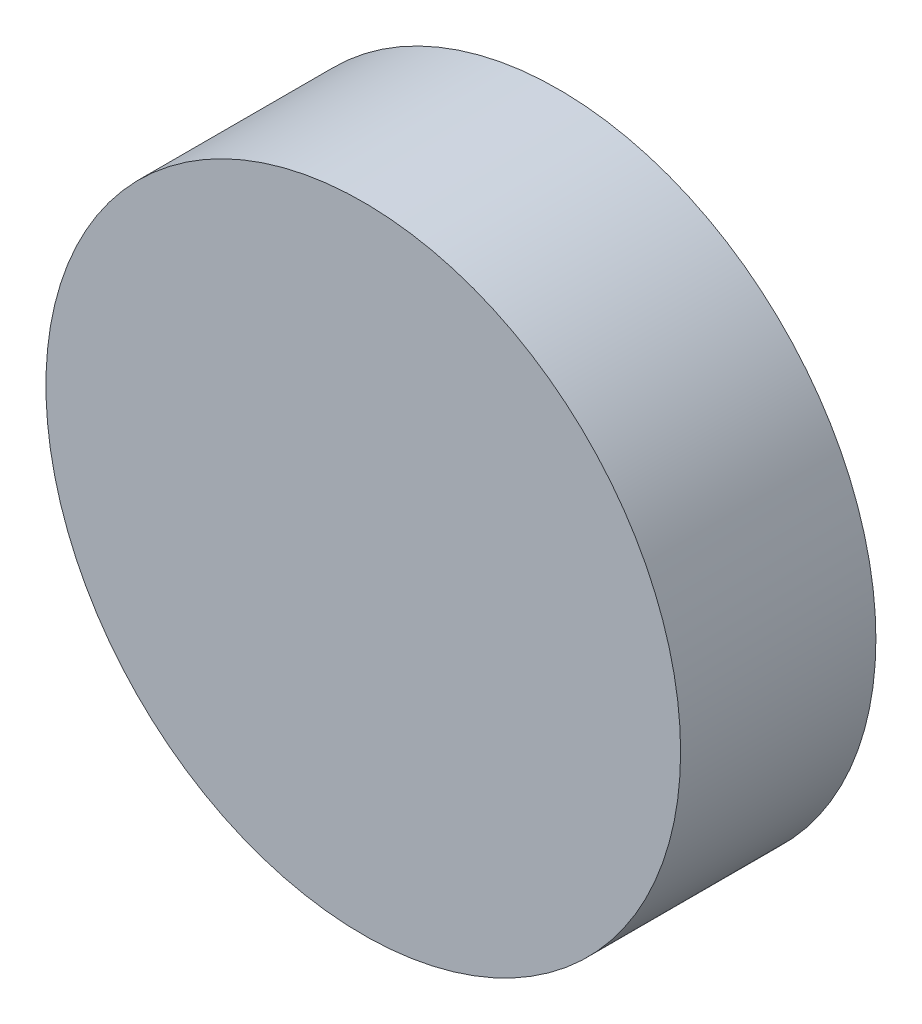
SolidWorks part; units mm, degrees
ref_plane "前视基准面" through (0, 0, 0) normal (0, 0, 1) x (1, 0, 0)
ref_plane "上视基准面" through (0, 0, 0) normal (0, 1, 0) x (1, 0, 0)
ref_plane "右视基准面" through (0, 0, 0) normal (1, 0, 0) x (0, 0, -1)
other "Configuration Table"
sketch "草图1" plane through (0, 0, 0) normal (0, 0, 1) x (1, 0, 0)
  circle A0 centre (0, 0) radius 32.5
  dimension "D1" = 65
extrude "凸台-拉伸1" add sketch "草图1" along normal blind 20
